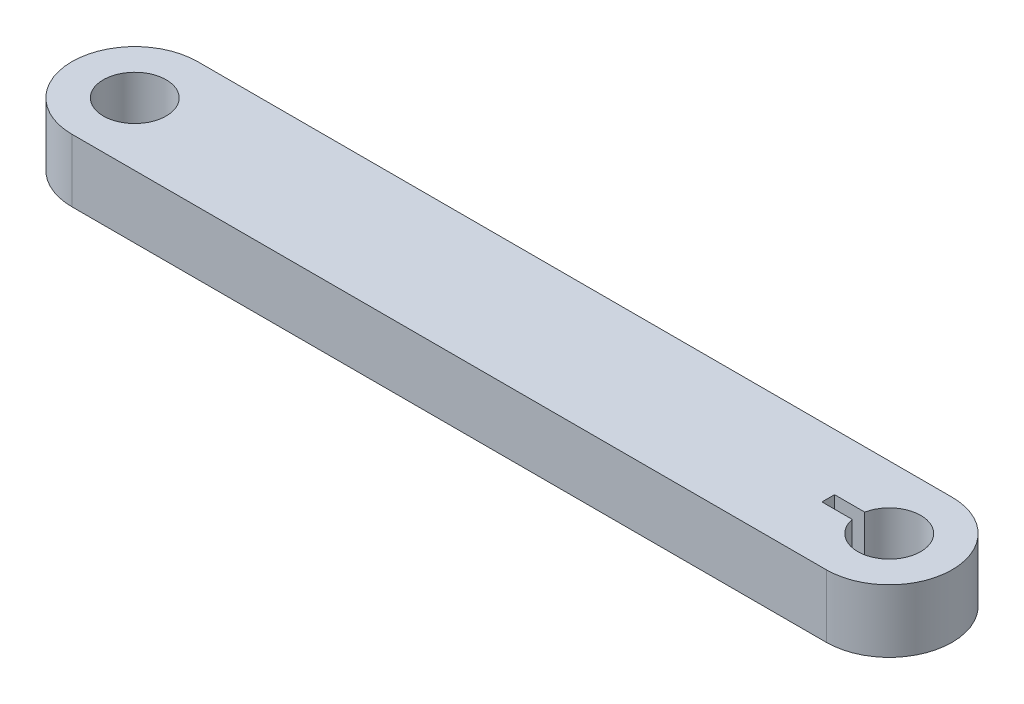
SolidWorks part; units mm, degrees
ref_plane "Front Plane" through (0, 0, 0) normal (0, 0, 1) x (1, 0, 0)
ref_plane "Top Plane" through (0, 0, 0) normal (0, 1, 0) x (1, 0, 0)
ref_plane "Right Plane" through (0, 0, 0) normal (1, 0, 0) x (0, 0, -1)
sketch "Sketch1" plane through (0, 0, 0) normal (0, 1, 0) x (1, 0, 0)
  line L0 (0, 0) -> (-76.2, 0) construction
  line L1 (0, -6.35) -> (-76.2, -6.35)
  line L2 (0, 6.35) -> (-76.2, 6.35)
  arc A0 (0, -6.35) -> (0, 6.35) centre (0, 0) ccw
  arc A1 (-76.2, 6.35) -> (-76.2, -6.35) centre (-76.2, 0) ccw
  point P3 (-38.1, 0)
  dimension "D2" = 6.35
  dimension "D1" = 76.2
extrude "Boss-Extrude1" add sketch "Sketch1" along normal blind 6.35
sketch "Sketch3" plane through (0, 6.35, 0) normal (0, 1, 0) x (1, 0, 0)
  line L1 (-3.1109, 0.635) -> (-6.1589, 0.635)
  line L2 (-3.1109, 0.635) -> (-3.1109, -0.635) construction
  line L3 (-3.1109, -0.635) -> (-6.1589, -0.635)
  line L4 (-6.1589, 0.635) -> (-6.1589, -0.635)
  circle A0 centre (0, 0) radius 3.175 construction
  arc A1 (-3.1109, -0.635) -> (-3.1109, 0.635) centre (0, 0) ccw
  point P7 (-3.1109, 0)
  dimension "D1" = 6.35
  dimension "D2" = 1.27
  dimension "D3" = 3.048
extrude "Cut-Extrude2" cut sketch "Sketch3" against normal through all
sketch "Sketch4" plane through (0, 6.35, 0) normal (0, 1, 0) x (1, 0, 0)
  circle A0 centre (-76.2, 0) radius 3.175
  arc A1 (-76.2, 6.35) -> (-76.2, -6.35) centre (-76.2, 0) ccw construction
  dimension "D1" = 6.35
extrude "Cut-Extrude3" cut sketch "Sketch4" against normal through all
